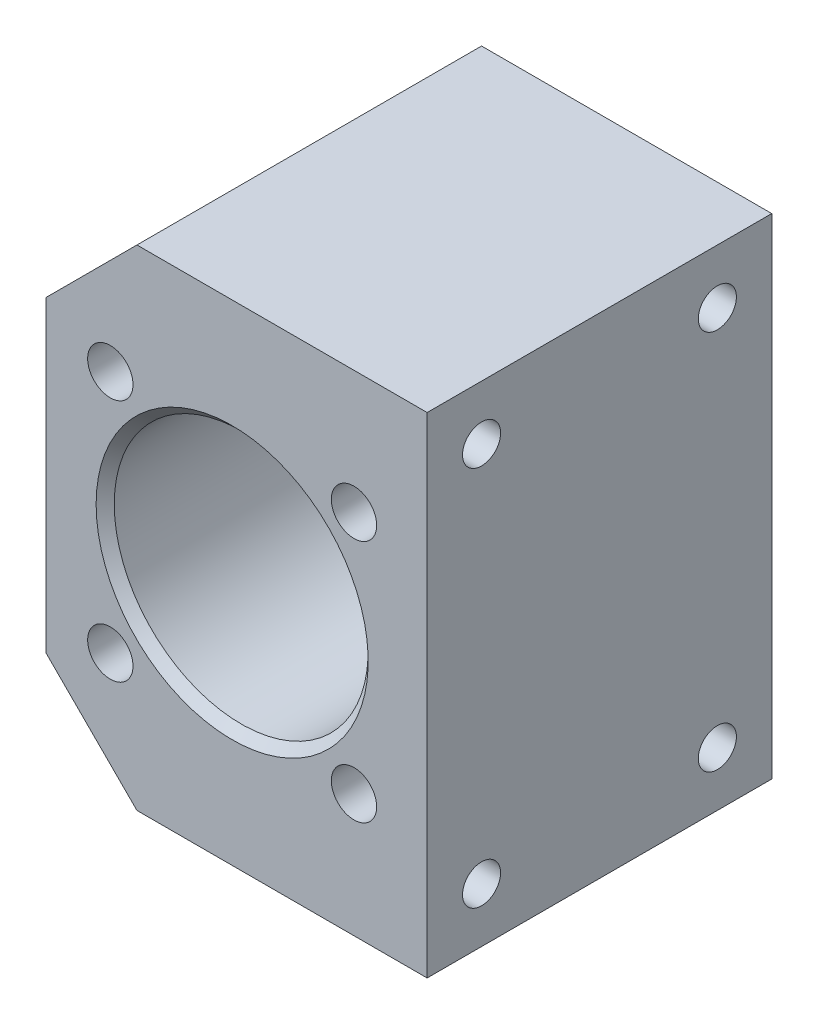
SolidWorks part; units mm, degrees
material "1.0037 (S235JR)"
ref_plane "Płaszczyzna przednia" through (0, 0, 0) normal (0, 0, 1) x (1, 0, 0)
ref_plane "Płaszczyzna górna" through (0, 0, 0) normal (0, 1, 0) x (1, 0, 0)
ref_plane "Płaszczyzna prawa" through (0, 0, 0) normal (1, 0, 0) x (0, 0, -1)
sketch "Szkic1" plane through (0, 0, 0) normal (0, 0, 1) x (1, 0, 0)
  line L0 (42, 27) -> (0, 27) construction
  line L1 (0, 0) -> (42, 0)
  line L2 (0, 0) -> (0, 54)
  line L3 (0, 54) -> (42, 54)
  line L4 (42, 0) -> (42, 54)
  circle A0 centre (20.5, 27) radius 14
  dimension "D3" = 28
  dimension "D1" = 42
  dimension "D2" = 54
  dimension "D4" = 20.5
extrude "Dodanie-wyciągnięcie1" add sketch "Szkic1" along normal blind 38
chamfer "Sfazowanie1" distance 1 angle 45 2 edges at (34.5, 27, 0) (34.5, 27, 38)
hole_wizard "Otwór gwintowany M6x1.01" positions "Szkic3" profile "Szkic2" tap size "M6x1.0" standard "Ansi Metric"
sketch "Szkic3" plane through (0, 0, 38) normal (0, 0, 1) x (1, 0, 0)
  circle A0 centre (7.065, 13.565) radius 3.3 construction
  circle A1 centre (33.935, 40.435) radius 3.3 construction
  circle A2 centre (33.935, 13.565) radius 3.3 construction
  point P0 (33.935, 40.435)
  point P2 (7.065, 40.435)
  point P5 (7.065, 13.565)
  point P7 (33.935, 13.565)
sketch "Szkic2" plane through (33.935, 40.435, 38) normal (1, 0, 0) x (0, -1, 0)
  line L0 (0, 0) -> (0, 18.5022)
  line L1 (0, 18.5022) -> (2.5, 17)
  line L2 (2.5, 17) -> (2.5, 0)
  line L5 (2.5, 0) -> (0, 0)
  line L10 (0, 18.5022) -> (-2.5, 17) construction
  line L11 (0, -6.35) -> (0, 107.95) construction
  dimension "Średnica wiertła gwintu" = 5
  dimension "Głębokość otworu gwintowanego" = 17
  dimension "Kąt wiertła" = 118
sketch "Szkic7" plane through (42, 0, 0) normal (1, 0, 0) x (0, 0, -1)
  line L8 (-6, 6) -> (-6, 48)
  line L9 (-6, 48) -> (-32, 48)
  line L10 (-32, 48) -> (-32, 6)
  line L11 (-32, 6) -> (-6, 6)
  line L12 (-6, 6) -> (-6, 48)
  line L13 (-6, 48) -> (-32, 48)
  line L14 (-32, 48) -> (-32, 6)
  line L15 (-32, 6) -> (-6, 6)
  dimension "D1" = 6
hole_wizard "Otwór gwintowany M5x0.81" positions "Szkic9" profile "Szkic8" tap size "M5x0.8" standard "Ansi Metric"
sketch "Szkic9" plane through (42, 0, 0) normal (1, 0, 0) x (0, 0, -1)
  point P0 (-32, 48)
  point P3 (-6, 48)
  point P6 (-6, 6)
  point P9 (-32, 6)
sketch "Szkic8" plane through (42, 48, 32) normal (0, 1, 0) x (0, 0, -1)
  line L0 (0, 0) -> (0, 26.2618)
  line L1 (0, 26.2618) -> (2.1, 25)
  line L2 (2.1, 25) -> (2.1, 0)
  line L5 (2.1, 0) -> (0, 0)
  line L10 (0, 26.2618) -> (-2.1, 25) construction
  line L11 (0, -6.35) -> (0, 107.95) construction
  dimension "Średnica wiertła gwintu" = 4.2
  dimension "Głębokość otworu gwintowanego" = 25
  dimension "Kąt wiertła" = 118
chamfer "Sfazowanie2" distance 10 angle 45 2 edges at (0, 0, 19) (0, 54, 19)
